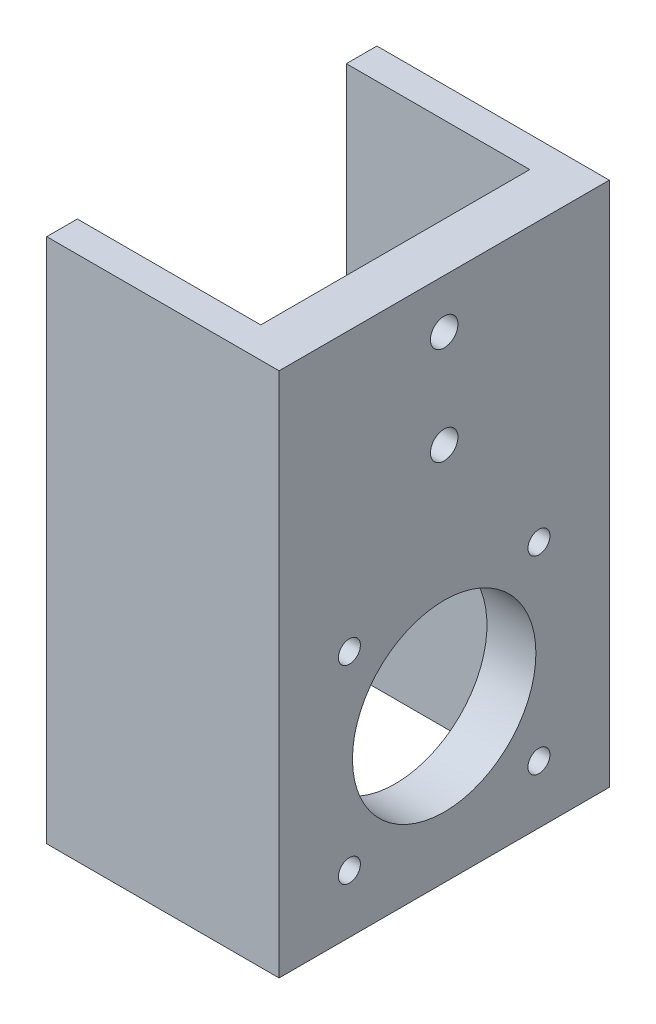
SolidWorks part; units mm, degrees
ref_plane "Front Plane" through (0, 0, 0) normal (0, 0, 1) x (1, 0, 0)
ref_plane "Top Plane" through (0, 0, 0) normal (0, 1, 0) x (1, 0, 0)
ref_plane "Right Plane" through (0, 0, 0) normal (1, 0, 0) x (0, 0, -1)
sketch "Sketch1" plane through (0, 0, 0) normal (0, 1, 0) x (1, 0, 0)
  line L1 (-10, -10) -> (10, -10)
  line L2 (-10, -10) -> (-10, 10)
  line L3 (-10, 10) -> (10, 10)
  line L4 (10, -10) -> (10, 10)
  line L5 (-10, -10) -> (10, 10) construction
  line L6 (-10, 10) -> (10, -10) construction
  line L7 (-14, 14) -> (14, 14)
  line L8 (-14, 14) -> (-14, -14)
  line L9 (-14, -14) -> (14, -14)
  line L10 (14, 14) -> (14, -14)
  line L11 (-14, 14) -> (14, -14) construction
  line L12 (-14, -14) -> (14, 14) construction
  point P0 (0, 0)
  point P5 (0, 0)
  dimension "D1" = 20
  dimension "D2" = 28
extrude "Boss-Extrude1" add sketch "Sketch1" along normal blind 40
sketch "Sketch2" plane through (-14, 0, 0) normal (-1, 0, 0) x (0, 0, 1)
  line L0 (0, 40) -> (0, 32)
  line L1 (0, 0) -> (0, 16)
  line L4 (-14, 0) -> (14, 0)
  line L5 (14, 0) -> (14, 40)
  line L6 (14, 40) -> (-14, 40)
  line L7 (-14, 40) -> (-14, 0)
  line L8 (-14, 0) -> (14, 0)
  line L9 (14, 0) -> (14, 40)
  line L10 (14, 40) -> (-14, 40)
  line L11 (-14, 40) -> (-14, 0)
  circle A0 centre (0, 32) radius 2.25
  circle A1 centre (0, 16) radius 2.25
  dimension "D3" = 4.5
  dimension "D5" = 4.5
  dimension "D2" = 8
  dimension "D4" = 16
  dimension "D1" = 0
extrude "Cut-Extrude1" cut sketch "Sketch2" against normal blind 30
sketch "Sketch5" plane through (-14, 0, 0) normal (-1, 0, 0) x (0, 0, 1)
  line L0 (0, 0) -> (0, -21)
  line L1 (0, -21) -> (-15.4998, -5.5002) construction
  line L2 (-25, -46) -> (25, -46)
  line L3 (-25, -46) -> (-25, 4)
  line L4 (-14, 0) -> (14, 0)
  line L5 (14, 0) -> (14, 40)
  line L6 (14, 40) -> (-14, 40)
  line L7 (-14, 40) -> (-14, 0)
  line L8 (-14, 0) -> (14, 0)
  line L9 (14, 0) -> (14, 40)
  line L10 (14, 40) -> (-14, 40)
  line L11 (-14, 40) -> (-14, 0)
  line L12 (-25, 4) -> (25, 4)
  line L13 (25, -46) -> (25, 4)
  line L14 (-25, -46) -> (25, 4) construction
  line L15 (-25, 4) -> (25, -46) construction
  line L16 (-15.4998, -5.5002) -> (15.4998, -5.5002) construction
  line L17 (15.4998, -5.5002) -> (15.4998, -36.4998) construction
  line L18 (15.4998, -36.4998) -> (-15.4998, -36.4998) construction
  circle A0 centre (-15.4998, -5.5002) radius 1.8
  circle A1 centre (15.4998, -5.5002) radius 1.8
  circle A2 centre (15.4998, -36.4998) radius 1.8
  circle A3 centre (-15.4998, -36.4998) radius 1.8
  circle A4 centre (0, -21) radius 15
  dimension "D5" = 3.6
  dimension "D6" = 30
  dimension "D2" = 21
  dimension "D3" = 50
  dimension "D4" = 21.92
  dimension "D1" = 0
extrude "Boss-Extrude2" add sketch "Sketch5" against normal up to surface (4 mm away) up to face at (-10, 16, -2.25)
sketch "Sketch6" plane through (0, 0, 0) normal (0, -1, 0) x (1, 0, 0)
  line L0 (-10, 14) -> (14, 14) construction
  line L1 (-10, 14) -> (14, 14)
  line L2 (-10, 14) -> (-10, -14)
  line L3 (-10, -14) -> (14, -14)
  line L4 (14, 14) -> (14, -14)
  dimension "D1" = 24
extrude "Cut-Extrude2" cut sketch "Sketch6" against normal blind 40
sketch "Sketch7" plane through (-14, 0, 0) normal (-1, 0, 0) x (0, 0, 1)
  line L0 (-10, 0) -> (10, 0)
  line L1 (-10, 0) -> (-10, 40)
  line L2 (-14, 40) -> (14, 40) construction
  line L3 (-10, 40) -> (10, 40)
  line L4 (10, 40) -> (10, 0)
  line L6 (-14, 40) -> (-10, 40)
  line L7 (-14, 40) -> (-14, 4)
  line L8 (-14, 4) -> (-10, 4)
  line L9 (-10, 40) -> (-10, 4)
  line L10 (14, 40) -> (10, 40)
  line L11 (14, 40) -> (14, 4)
  line L12 (14, 4) -> (10, 4)
  line L13 (10, 40) -> (10, 4)
  point P4 (0, 0)
  line M7 (-14, 40) -> (-14, 4)
  line M13 (14, 4) -> (14, 40)
  line M14 (14, 40) -> (-14, 40)
  dimension "D1" = 20
  dimension "D2" = 36
  dimension "D3" = 4
  dimension "D4" = 36
  dimension "D5" = 4
extrude "Cut-Extrude3" cut sketch "Sketch7" against normal blind 4 contours L8 L1 M7 M14 | L12 L4 M13 M14
sketch "Sketch8" plane through (-14, 0, 0) normal (-1, 0, 0) x (0, 0, 1)
  line L1 (-25, 4) -> (-10, 4)
  line L2 (-25, 4) -> (-25, 40)
  line L3 (-25, 40) -> (-10, 40)
  line L4 (-10, 4) -> (-10, 40)
  line L5 (10, 40) -> (25, 40)
  line L6 (10, 40) -> (10, 4)
  line L7 (10, 4) -> (25, 4)
  line L8 (25, 40) -> (25, 4)
extrude "Boss-Extrude3" add sketch "Sketch8" against normal up to vertex (4 mm away)
sketch "Sketch11" plane through (-14, 0, 0) normal (-1, 0, 0) x (0, 0, 1)
  line L0 (-25, -46) -> (25, -46) construction
  line L1 (25, -46) -> (25, 40) construction
  line L2 (-25, 40) -> (25, 40) construction
  line L3 (-25, -46) -> (-25, 40) construction
  line L4 (-25, -46) -> (25, -46)
  line L5 (25, -46) -> (25, 40)
  line L6 (-25, 40) -> (25, 40)
  line L7 (-25, -46) -> (-25, 40)
  circle A1 centre (15.4998, -5.5002) radius 1.8
  circle A2 centre (15.4998, -5.5002) radius 1.8
  circle A3 centre (15.4998, -36.4998) radius 1.8
  circle A4 centre (15.4998, -36.4998) radius 1.8
  circle A5 centre (-15.4998, -36.4998) radius 1.8
  circle A6 centre (-15.4998, -36.4998) radius 1.8
  circle A7 centre (0, -21) radius 15
  circle A8 centre (0, -21) radius 15
  circle A9 centre (0, 32) radius 2.25
  circle A10 centre (0, 32) radius 2.25
  circle A11 centre (0, 16) radius 2.25
  circle A12 centre (0, 16) radius 2.25
  circle A13 centre (-15.4998, -5.5002) radius 1.8
  circle A14 centre (-15.4998, -5.5002) radius 1.8
  dimension "D1" = 0
  dimension "D2" = 0
  dimension "D3" = 0
  dimension "D4" = 0
  dimension "D5" = 0
  dimension "D6" = 0
  dimension "D7" = 0
extrude "Boss-Extrude4" add sketch "Sketch11" along normal blind 4
sketch "Sketch13" plane through (0, 0, 25) normal (0, 0, 1) x (1, 0, 0)
  line L4 (-18, -46) -> (-10, -46)
  line L5 (-10, -46) -> (-10, 40)
  line L6 (-10, 40) -> (-18, 40)
  line L7 (-18, 40) -> (-18, -46)
  line L8 (-18, -46) -> (-10, -46)
  line L9 (-10, -46) -> (-10, 40)
  line L10 (-10, 40) -> (-18, 40)
  line L11 (-18, 40) -> (-18, -46)
  dimension "D1" = 0
extrude "Boss-Extrude5" add sketch "Sketch13" along normal blind 2
sketch "Sketch14" plane through (0, 0, -25) normal (0, 0, -1) x (-1, 0, 0)
  line L4 (10, 40) -> (10, -46)
  line L5 (10, -46) -> (18, -46)
  line L6 (18, -46) -> (18, 40)
  line L7 (18, 40) -> (10, 40)
  line L8 (10, 40) -> (10, -46)
  line L9 (10, -46) -> (18, -46)
  line L10 (18, -46) -> (18, 40)
  line L11 (18, 40) -> (10, 40)
  dimension "D1" = 0
extrude "Boss-Extrude6" add sketch "Sketch14" along normal blind 2
sketch "Sketch16" plane through (0, 0, -27) normal (0, 0, -1) x (-1, 0, 0)
  line L1 (18, 40) -> (48, 40)
  line L2 (18, 40) -> (18, -46)
  line L3 (18, -46) -> (48, -46)
  line L4 (48, 40) -> (48, -46)
  dimension "D1" = 30
extrude "Boss-Extrude7" add sketch "Sketch16" against normal blind 5
mirror "Mirror1" about plane through (0, 0, 0) normal (0, 0, 1) of "Boss-Extrude7"
